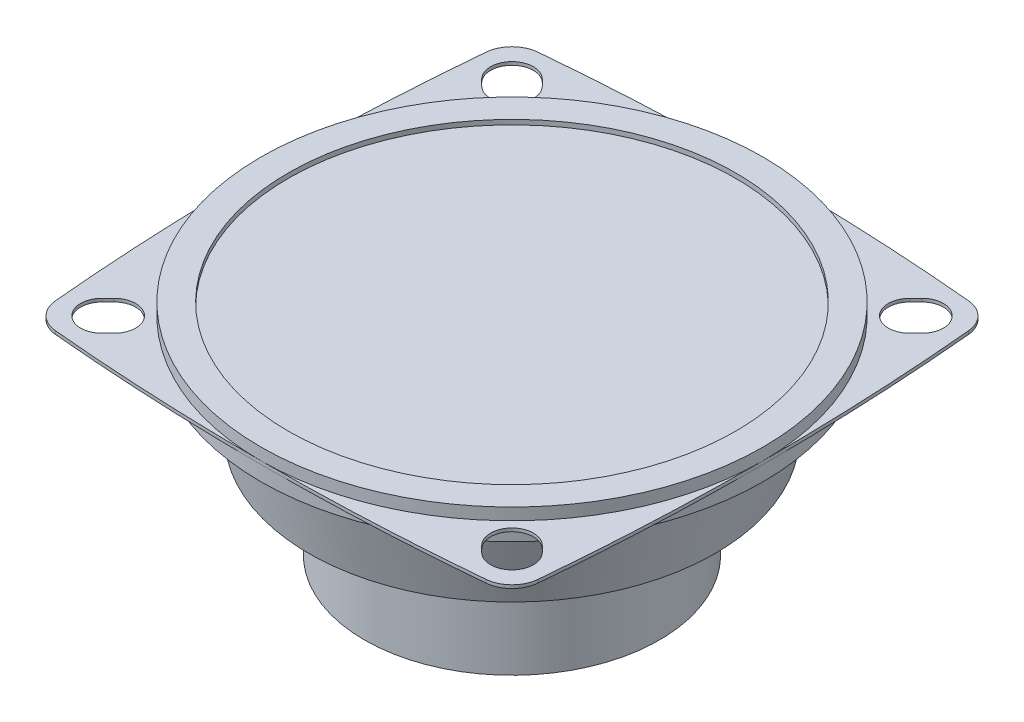
SolidWorks part; units mm, degrees
ref_plane "Front Plane" through (0, 0, 0) normal (0, 0, 1) x (1, 0, 0)
ref_plane "Top Plane" through (0, 0, 0) normal (0, 1, 0) x (1, 0, 0)
ref_plane "Right Plane" through (0, 0, 0) normal (1, 0, 0) x (0, 0, -1)
sketch "Sketch1" plane through (0, 0, 0) normal (0, 0, 1) x (1, 0, 0)
  line L0 (0, 0) -> (0, 23)
  line L1 (0, 23) -> (26.38, 23)
  line L2 (26.38, 19.84) -> (23.325, 19.84)
  line L3 (23.325, 19.84) -> (21.35, 10.8)
  line L4 (21.35, 10.8) -> (15.5, 9)
  line L5 (15.5, 9) -> (15.5, 0)
  line L6 (15.5, 0) -> (0, 0)
  line L7 (26.38, 23) -> (26.38, 19.84)
  dimension "D1" = 26.38
  dimension "D2" = 15.5
  dimension "D3" = 9
  dimension "D4" = 23.325
  dimension "D5" = 3.16
  dimension "D6" = 21.35
  dimension "D7" = 12.2
  dimension "D8" = 23
revolve "Revolve1" add sketch "Sketch1" angle 360 about L0
ref_plane "Plane1" through (0, 21.75, 0) normal (0, 1, 0) x (1, 0, 0)
sketch "Sketch2" plane through (0, 21.75, 0) normal (0, 1, 0) x (1, 0, 0)
  line L0 (-21.5314, 21.5314) -> (-20.895, 20.895) construction
  line L1 (21.2132, -21.2132) -> (-21.2132, -21.2132) construction
  line L2 (21.2132, -21.2132) -> (21.2132, 21.2132) construction
  line L3 (21.2132, 21.2132) -> (-21.2132, 21.2132) construction
  line L4 (-21.2132, -21.2132) -> (-21.2132, 21.2132) construction
  line L5 (21.2132, -21.2132) -> (-21.2132, 21.2132) construction
  line L6 (21.2132, 21.2132) -> (-21.2132, -21.2132) construction
  line L7 (-19.9404, 23.1224) -> (-19.304, 22.486)
  line L8 (-23.1224, 19.9404) -> (-22.486, 19.304)
  line L9 (21.5314, 21.5314) -> (20.895, 20.895) construction
  line L10 (23.1224, 19.9404) -> (22.486, 19.304)
  line L11 (19.9404, 23.1224) -> (19.304, 22.486)
  line L12 (21.5314, -21.5314) -> (20.895, -20.895) construction
  line L13 (19.9404, -23.1224) -> (19.304, -22.486)
  line L14 (23.1224, -19.9404) -> (22.486, -19.304)
  line L15 (-21.5314, -21.5314) -> (-20.895, -20.895) construction
  line L16 (-23.1224, -19.9404) -> (-22.486, -19.304)
  line L17 (-19.9404, -23.1224) -> (-19.304, -22.486)
  line L18 (-26.38, 0) -> (26.38, 0) construction
  line L19 (25.1023, -25.1023) -> (-25.1023, -25.1023) construction
  line L20 (25.1023, -25.1023) -> (25.1023, 25.1023) construction
  line L21 (25.1023, 25.1023) -> (-25.1023, 25.1023) construction
  line L22 (-25.1023, -25.1023) -> (-25.1023, 25.1023) construction
  line L23 (25.1023, -25.1023) -> (-25.1023, 25.1023) construction
  line L24 (25.1023, 25.1023) -> (-25.1023, -25.1023) construction
  line L25 (0, 26.38) -> (0, -26.38) construction
  arc A0 (-19.9404, 23.1224) -> (-23.1224, 19.9404) centre (-21.5314, 21.5314) ccw
  arc A1 (-22.486, 19.304) -> (-19.304, 22.486) centre (-20.895, 20.895) ccw
  arc A2 (23.1224, 19.9404) -> (19.9404, 23.1224) centre (21.5314, 21.5314) ccw
  arc A3 (19.304, 22.486) -> (22.486, 19.304) centre (20.895, 20.895) ccw
  arc A4 (19.9404, -23.1224) -> (23.1224, -19.9404) centre (21.5314, -21.5314) ccw
  arc A5 (22.486, -19.304) -> (19.304, -22.486) centre (20.895, -20.895) ccw
  arc A6 (-23.1224, -19.9404) -> (-19.9404, -23.1224) centre (-21.5314, -21.5314) ccw
  arc A7 (-19.304, -22.486) -> (-22.486, -19.304) centre (-20.895, -20.895) ccw
  circle A9 centre (0, 0) radius 26.38 construction
  circle A10 centre (0, 0) radius 26.38 construction
  arc A17 (25.1023, -25.1023) -> (25.1023, 25.1023) centre (-220.8427, 0) ccw
  arc A18 (25.1023, 25.1023) -> (-25.1023, 25.1023) centre (0, -220.8427) ccw
  arc A19 (-25.1023, -25.1023) -> (25.1023, -25.1023) centre (0, 220.8427) ccw
  arc A20 (-25.1023, 25.1023) -> (-25.1023, -25.1023) centre (220.8427, 0) ccw
  point P0 (0, 0)
  point P7 (-21.2132, 21.2132)
  point P14 (21.2132, 21.2132)
  point P21 (21.2132, -21.2132)
  point P28 (-21.2132, -21.2132)
  point P34 (0, 0)
  dimension "D3" = 0.9
  dimension "D1" = 60
  dimension "D2" = 4.5
  dimension "D4" = 71
extrude "Boss-Extrude1" add sketch "Sketch2" against normal blind 0.34
fillet "Fillet1" radius 3 4 edges at (-25.1023, 21.58, 25.1023) (25.1023, 21.58, 25.1023) (25.1023, 21.58, -25.1023) (-25.1023, 21.58, -25.1023)
sketch "Sketch3" plane through (0, 23, 0) normal (0, 1, 0) x (1, 0, 0)
  circle A0 centre (0, 0) radius 23.5
  dimension "D1" = 47
extrude "Cut-Extrude1" cut sketch "Sketch3" against normal blind 0.5
